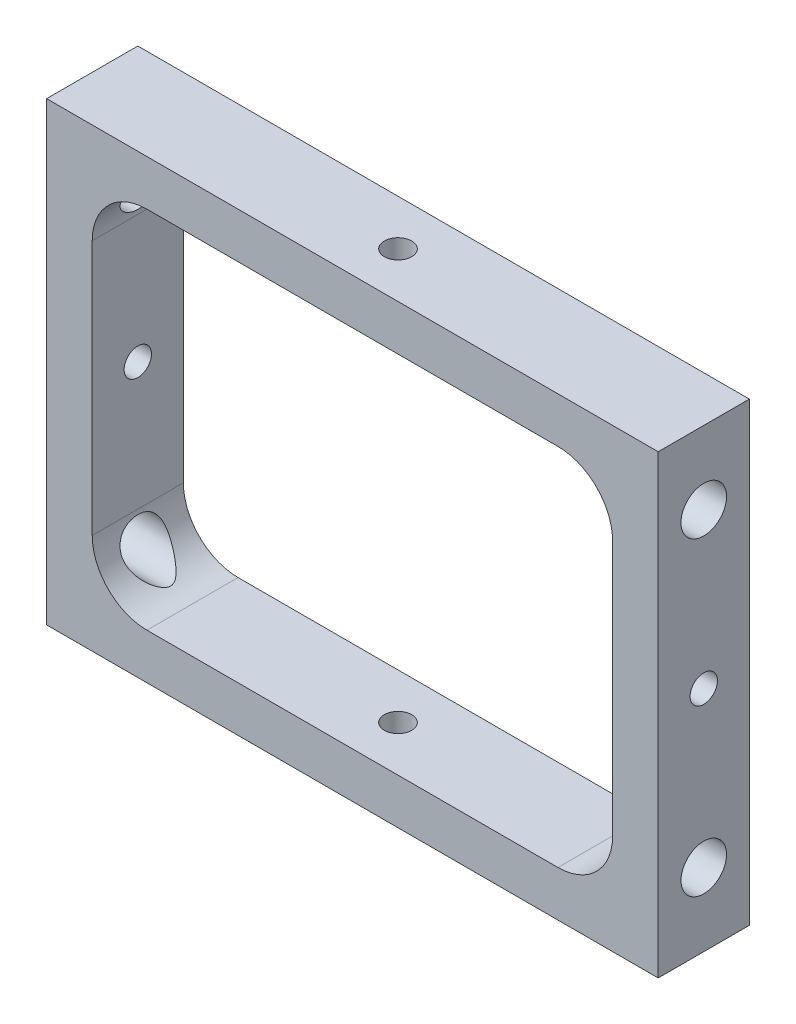
SolidWorks part; units mm, degrees
ref_plane "前视基准面" through (0, 0, 0) normal (0, 0, 1) x (1, 0, 0)
ref_plane "上视基准面" through (0, 0, 0) normal (0, 1, 0) x (1, 0, 0)
ref_plane "右视基准面" through (0, 0, 0) normal (1, 0, 0) x (0, 0, -1)
sketch "草图1" plane through (0, 0, 0) normal (0, 0, 1) x (1, 0, 0)
  line L0 (11, 45) -> (56.09, 45)
  line L1 (0, 0) -> (67.09, 0)
  line L2 (0, 0) -> (0, 50)
  line L3 (0, 50) -> (67.09, 50)
  line L4 (67.09, 0) -> (67.09, 50)
  line L5 (62.09, 11) -> (62.09, 39)
  line L6 (11, 5) -> (56.09, 5)
  line L7 (5, 11) -> (5, 39)
  line L8 (5, 45) -> (62.09, 45) construction
  line L9 (62.09, 5) -> (62.09, 45) construction
  line L10 (5, 5) -> (62.09, 5) construction
  line L11 (5, 5) -> (5, 45) construction
  arc A0 (56.09, 45) -> (62.09, 39) centre (56.09, 39) cw
  arc A1 (62.09, 11) -> (56.09, 5) centre (56.09, 11) cw
  arc A2 (11, 5) -> (5, 11) centre (11, 11) cw
  arc A3 (5, 39) -> (11, 45) centre (11, 39) cw
  dimension "D4" = 6
  dimension "D1" = 50
  dimension "D2" = 67.09
  dimension "D3" = 5
extrude "凸台-拉伸1" add sketch "草图1" along normal blind 10
sketch "草图2" plane through (0, 0, 0) normal (-1, 0, 0) x (0, 0, 1)
  line L0 (5, 0) -> (5, 50) construction
  line L1 (10, 0) -> (0, 0) construction
  line L2 (10, 50) -> (0, 50) construction
  line L3 (10, 25) -> (0, 25) construction
  line L4 (10, 50) -> (10, 0) construction
  line L5 (0, 50) -> (0, 0) construction
  circle A0 centre (5, 42) radius 2.5
  circle A1 centre (5, 8) radius 2.5
  circle A2 centre (5, 25) radius 1.5
  dimension "D1" = 8
extrude "切除-拉伸1" cut sketch "草图2" against normal through all
sketch "草图3" plane through (0, 0, 0) normal (0, -1, 0) x (1, 0, 0)
  line L0 (33.545, 10) -> (33.545, 0) construction
  line L1 (0, 10) -> (67.09, 10) construction
  line L2 (0, 0) -> (67.09, 0) construction
  line L3 (36, 5) -> (51.2856, 5) construction
  circle A0 centre (33.545, 5) radius 1.5
extrude "切除-拉伸2" cut sketch "草图3" against normal through all
